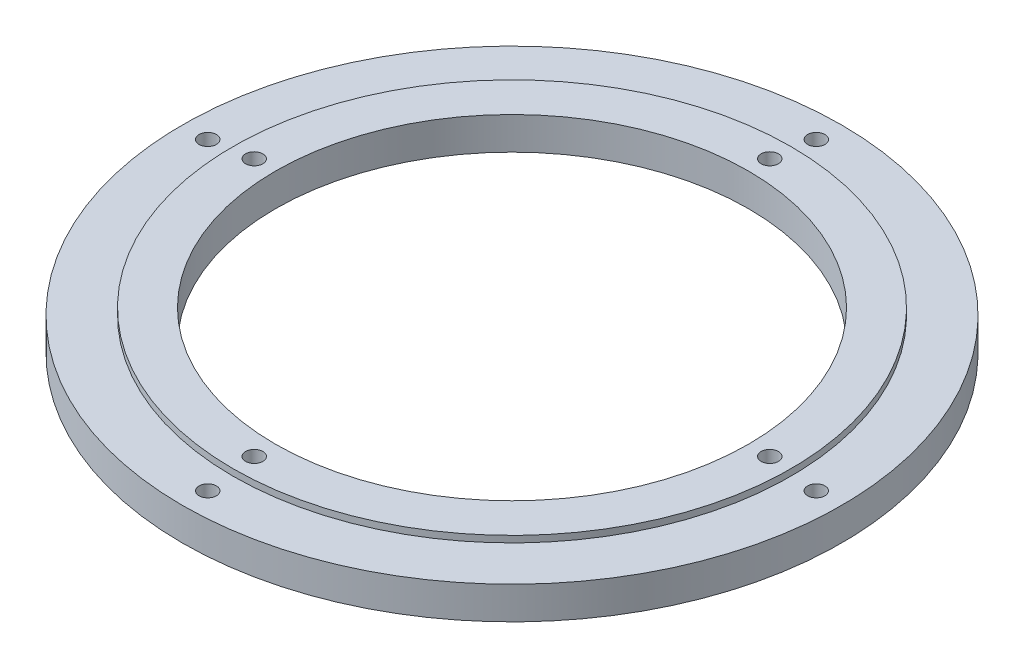
SolidWorks part; units mm, degrees
ref_plane "前视基准面" through (0, 0, 0) normal (0, 0, 1) x (1, 0, 0)
ref_plane "上视基准面" through (0, 0, 0) normal (0, 1, 0) x (1, 0, 0)
ref_plane "右视基准面" through (0, 0, 0) normal (1, 0, 0) x (0, 0, -1)
other "Configuration Table"
sketch "草图1" plane through (0, 0, 0) normal (0, 1, 0) x (1, 0, 0)
  line L0 (0, 85.5) -> (0, 72.5)
  circle A0 centre (0, 0) radius 72.5
  circle A1 centre (0, 0) radius 85.5
  circle A2 centre (0, 0) radius 101
  circle A3 centre (0, 79) radius 2.65
  circle A4 centre (79, 0) radius 2.65
  circle A5 centre (0, -79) radius 2.65
  circle A6 centre (-79, 0) radius 2.65
  point P19 (0, 0)
  dimension "D1" = 145
  dimension "D3" = 202
  dimension "D4" = 5.3
  dimension "D2" = 13
  dimension "D5" = 4
extrude "凸台-拉伸2" add sketch "草图1" along normal blind 10
ref_plane "基准面1" through (0, -2, 0) normal (0, -1, 0) x (-1, 0, 0)
sketch "草图2" plane through (0, -2, 0) normal (0, -1, 0) x (-1, 0, 0)
  line L0 (0, 85.5) -> (0, 101)
  circle A0 centre (0, 0) radius 101
  circle A1 centre (0, 0) radius 85.5
  circle A2 centre (0, 93.25) radius 2.65
  circle A3 centre (93.25, 0) radius 2.65
  circle A4 centre (0, -93.25) radius 2.65
  circle A5 centre (-93.25, 0) radius 2.65
  point P18 (0, 0)
  dimension "D1" = 5.3
  dimension "D2" = 4
extrude "凸台-拉伸3" add sketch "草图2" against normal blind 10
